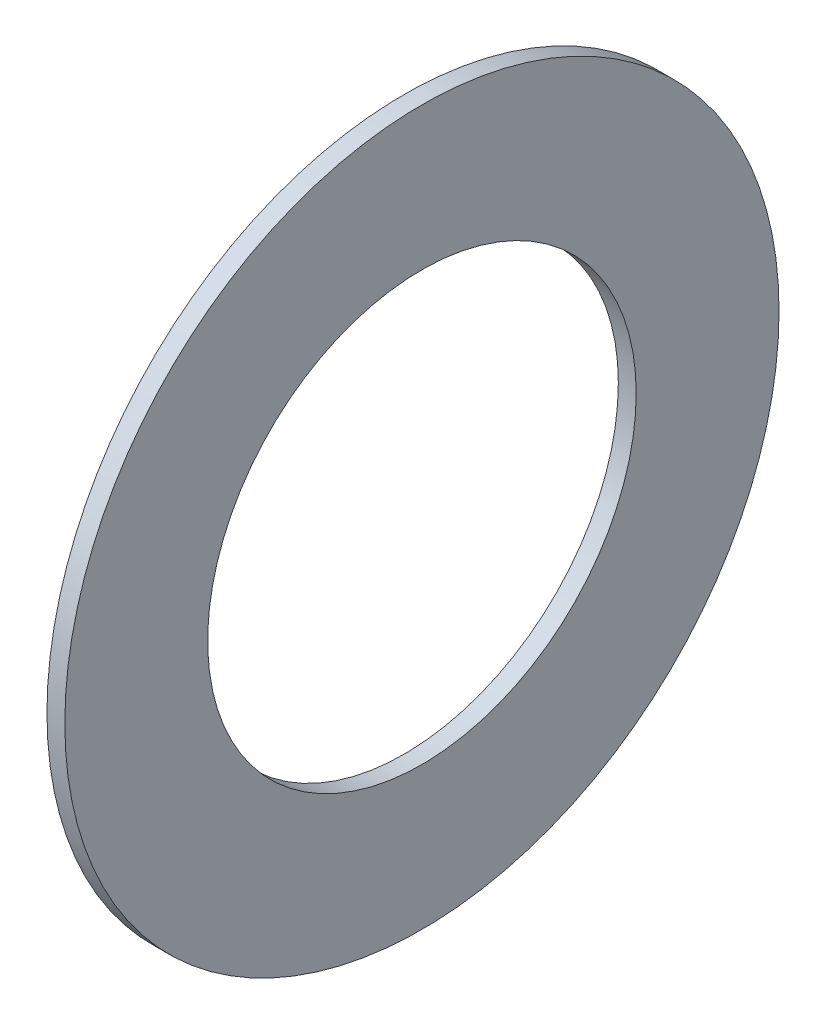
SolidWorks part; units mm, degrees
material "Plain Carbon Steel"
ref_plane "Front Plane" through (0, 0, 0) normal (0, 0, 1) x (1, 0, 0)
ref_plane "Top Plane" through (0, 0, 0) normal (0, 1, 0) x (1, 0, 0)
ref_plane "Right Plane" through (0, 0, 0) normal (1, 0, 0) x (0, 0, -1)
sketch "Sketch1" plane through (0, 0, 0) normal (1, 0, 0) x (0, 0, -1)
  circle A0 centre (0, 0) radius 9.525
  circle A1 centre (0, 0) radius 15.875
  dimension "D1" = 19.05
  dimension "D2" = 31.75
extrude "Extrude1" add sketch "Sketch1" along normal blind 0.7937
